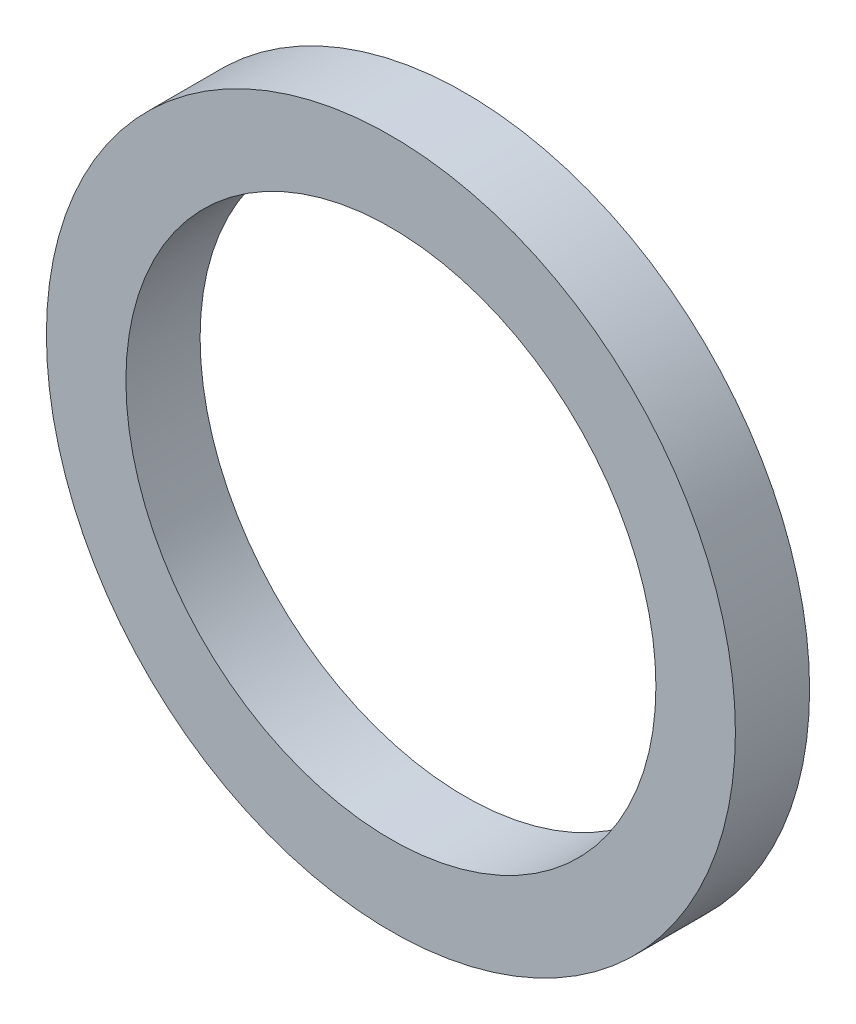
SolidWorks part; units mm, degrees
material "Stainless Steel (ferritic)"
ref_plane "Front Plane" through (0, 0, 0) normal (0, 0, 1) x (1, 0, 0)
ref_plane "Top Plane" through (0, 0, 0) normal (0, 1, 0) x (1, 0, 0)
ref_plane "Right Plane" through (0, 0, 0) normal (1, 0, 0) x (0, 0, -1)
sketch "Sketch1" plane through (0, 0, 0) normal (0, 0, 1) x (1, 0, 0)
  circle A0 centre (0, 0) radius 32.5
  circle A1 centre (0, 0) radius 25
  dimension "D1" = 65
  dimension "D2" = 50
extrude "Boss-Extrude1" add sketch "Sketch1" along normal blind 7
